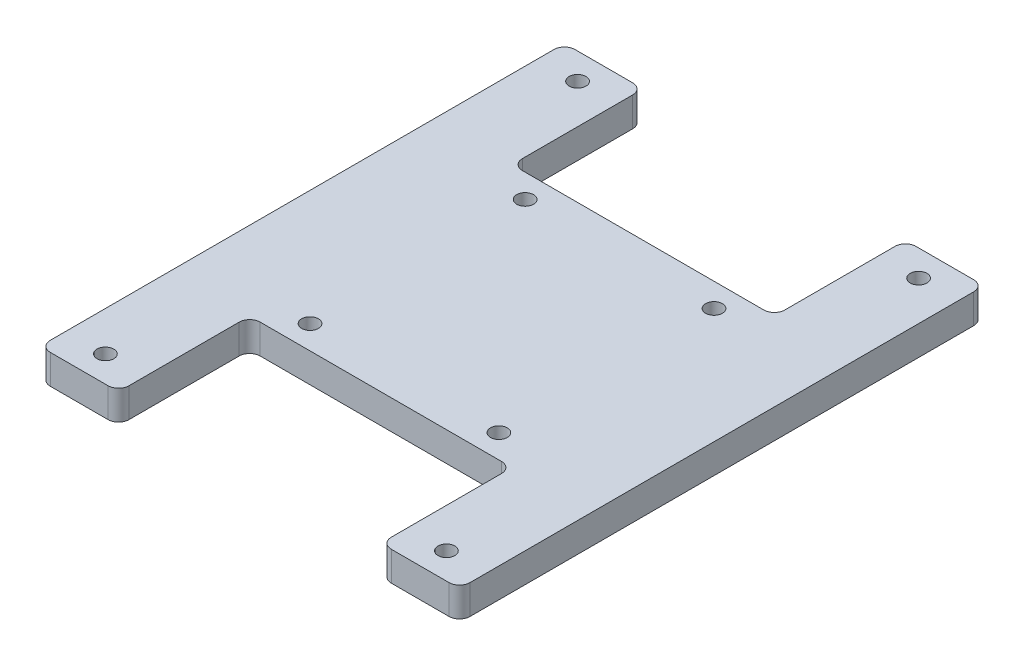
SolidWorks part; units mm, degrees
material "t5ハニカムプラダン"
ref_plane "正面" through (0, 0, 0) normal (0, 0, 1) x (1, 0, 0)
ref_plane "平面" through (0, 0, 0) normal (0, 1, 0) x (1, 0, 0)
ref_plane "右側面" through (0, 0, 0) normal (1, 0, 0) x (0, 0, -1)
sketch "ｽｹｯﾁ1" plane through (0, 0, 0) normal (0, 1, 0) x (1, 0, 0)
  line L0 (0, 0) -> (0, 50) construction
  line L1 (-40, 50) -> (40, 50)
  line L2 (-40, 50) -> (-40, -50)
  line L3 (-40, -50) -> (40, -50)
  line L4 (40, 50) -> (40, -50)
  line L5 (-40, 50) -> (40, -50) construction
  line L6 (-40, -50) -> (40, 50) construction
  line L7 (0, 0) -> (40, 0) construction
  line L8 (0, 45) -> (32.5, 45) construction
  line L9 (-25, 25) -> (25, 25)
  line L10 (-25, 25) -> (-25, 50)
  line L11 (-25, 50) -> (25, 50)
  line L12 (25, 25) -> (25, 50)
  line L13 (-25, 25) -> (25, 50) construction
  line L14 (-25, 50) -> (25, 25) construction
  line L15 (-25, -50) -> (25, -25) construction
  line L16 (-25, -25) -> (25, -50) construction
  line L17 (0, -45) -> (32.5, -45) construction
  line L18 (25, -25) -> (25, -50)
  line L19 (-25, -50) -> (25, -50)
  line L20 (-25, -25) -> (-25, -50)
  line L21 (-25, -25) -> (25, -25)
  line L22 (-40, -50) -> (40, -50)
  circle A0 centre (32.5, 45) radius 1.6
  circle A1 centre (-32.5, 45) radius 1.6
  circle A2 centre (-32.5, -45) radius 1.6
  circle A3 centre (32.5, -45) radius 1.6
  point P0 (0, 0)
  point P8 (0, 37.5)
  point P28 (0, -37.5)
  dimension "D5" = 3.2
  dimension "D1" = 100
  dimension "D2" = 80
  dimension "D3" = 25
  dimension "D4" = 50
  dimension "D6" = 5
  dimension "D7" = 65
extrude "ﾎﾞｽ - 押し出し1" add sketch "ｽｹｯﾁ1" along normal blind 5.6 contours L20 L21 L18 L3 L4 L1 L12 L9 L10 L2 A1 A0 A2 A3
sketch "ｽｹｯﾁ2" plane through (0, 5.6, 0) normal (0, 1, 0) x (1, 0, 0)
  line L0 (0, 20.5) -> (0, 0) construction
  line L1 (-18, 20.5) -> (18, 20.5) construction
  line L2 (-18, 20.5) -> (-18, -20.5) construction
  line L3 (-18, -20.5) -> (18, -20.5) construction
  line L4 (18, 20.5) -> (18, -20.5) construction
  line L5 (-18, 20.5) -> (18, -20.5) construction
  line L6 (-18, -20.5) -> (18, 20.5) construction
  line L7 (0, 0) -> (18, 0) construction
  line L8 (-18, 20.5) -> (-18, -20.5) construction
  circle A0 centre (18, 20.5) radius 1.6
  circle A1 centre (18, -20.5) radius 1.6
  circle A2 centre (-18, -20.5) radius 1.6
  circle A3 centre (-18, 20.5) radius 1.6
  point P0 (0, 0)
  dimension "D3" = 3.2
  dimension "D1" = 36
  dimension "D2" = 41
extrude "ｶｯﾄ - 押し出し1" cut sketch "ｽｹｯﾁ2" against normal through all
fillet "ﾌｨﾚｯﾄ1" radius 2 12 edges at (25, 2.8, -25) (-40, 2.8, -50) (-25, 2.8, -50) (-25, 2.8, -25) (25, 2.8, -50) (40, 2.8, -50) (25, 2.8, 50) (25, 2.8, 25) (40, 2.8, 50) (-25, 2.8, 25) (-25, 2.8, 50) (-40, 2.8, 50)
